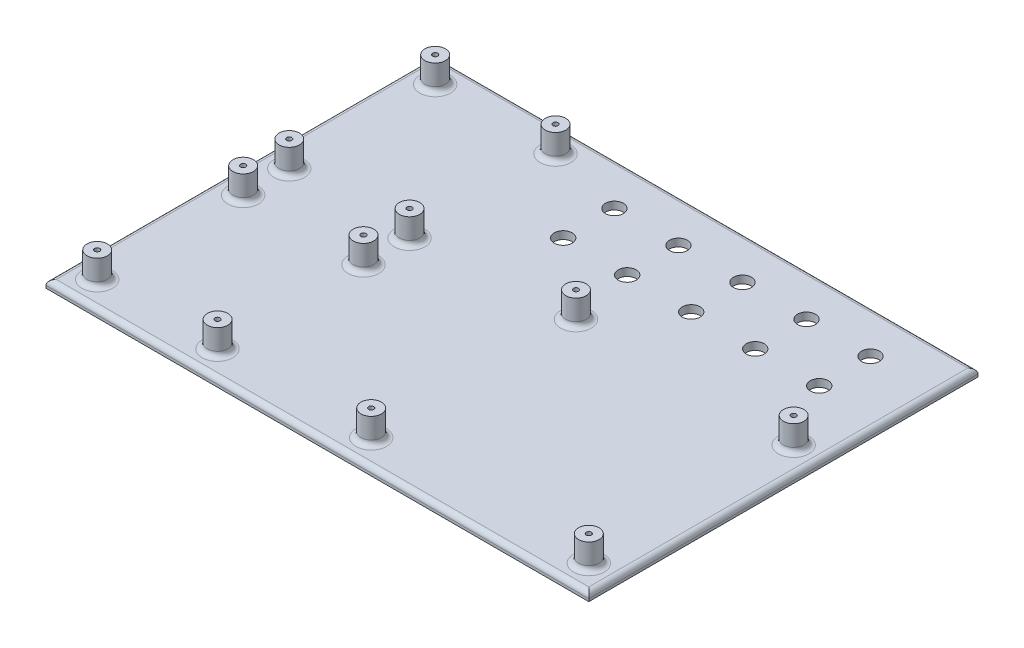
SolidWorks part; units mm, degrees
ref_plane "Front Plane" through (0, 0, 0) normal (0, 0, 1) x (1, 0, 0)
ref_plane "Top Plane" through (0, 0, 0) normal (0, 1, 0) x (1, 0, 0)
ref_plane "Right Plane" through (0, 0, 0) normal (1, 0, 0) x (0, 0, -1)
sketch "Sketch1" plane through (0, 0, 0) normal (0, 1, 0) x (1, 0, 0)
  circle A0 centre (0, 0) radius 4
  circle A1 centre (0, 80) radius 4
  circle A2 centre (85, 80) radius 4
  circle A3 centre (85, 0) radius 4
  circle A4 centre (-107, 0) radius 4
  circle A5 centre (-60, 0) radius 4
  circle A6 centre (-60, 57) radius 4
  circle A7 centre (-107, 57) radius 4
  circle A8 centre (-107, 132) radius 4
  circle A9 centre (-60, 132) radius 4
  circle A10 centre (-60, 75) radius 4
  circle A11 centre (-107, 75) radius 4
  dimension "D1" = 8
  dimension "D2" = 85
  dimension "D3" = 80
  dimension "D4" = 47
  dimension "D5" = 57
  dimension "D6" = 60
  dimension "D8" = 18
  dimension "D7" = 2
extrude "Boss-Extrude1" add sketch "Sketch1" along normal blind 10
sketch "Sketch2" plane through (0, 0, 0) normal (0, 1, 0) x (1, 0, 0)
  line L1 (-117, 142) -> (95, 142)
  line L2 (-117, 142) -> (-117, -10)
  line L3 (-117, -10) -> (95, -10)
  line L4 (95, 142) -> (95, -10)
  circle A0 centre (85, 0) radius 4 construction
  circle A1 centre (-60, 132) radius 4 construction
  circle A2 centre (-107, 0) radius 4 construction
  point P4 (131.0128, -48.0077)
  dimension "D1" = 10
  dimension "D2" = 10
  dimension "D3" = 10
  dimension "D4" = 10
extrude "Boss-Extrude2" add sketch "Sketch2" against normal blind 3
fillet "Fillet1" radius 2 16 edges at (-11, 0, -142) (95, 0, -66) (-11, 0, 10) (-117, 0, -66) (0, 0, 4) (0, 0, -76) (85, 0, -76) (85, 0, 4) (-60, 0, 4) (-60, 0, -53) (-107, 0, 4) (-107, 0, -53) (-60, 0, -71) (-60, 0, -128) (-107, 0, -71) (-107, 0, -128)
sketch "Sketch3" plane through (0, 0, 0) normal (0, 1, 0) x (1, 0, 0)
  circle A0 centre (-30, 125) radius 3.5
  circle A1 centre (-30, 105) radius 3.5
  circle A2 centre (0, 80) radius 4 construction
  circle A3 centre (-60, 132) radius 4 construction
  circle A4 centre (-5, 105) radius 3.5
  circle A5 centre (-5, 125) radius 3.5
  circle A6 centre (20, 105) radius 3.5
  circle A7 centre (20, 125) radius 3.5
  circle A8 centre (45, 105) radius 3.5
  circle A9 centre (45, 125) radius 3.5
  circle A10 centre (70, 105) radius 3.5
  circle A11 centre (70, 125) radius 3.5
  dimension "D2" = 7
  dimension "D4" = 30
  dimension "D6" = 25
  dimension "D1" = 20
  dimension "D3" = 25
  dimension "D5" = 5
extrude "Cut-Extrude1" cut sketch "Sketch3" against normal through all both and the other way through all
hole_wizard "Ø2.0mm Dowel Hole1" positions "Sketch4" profile "Sketch5" hole size "Ø2.0" standard "ANSI Metric" end condition through all
sketch "Sketch4" plane through (0, 10, 0) normal (0, 1, 0) x (1, 0, 0)
  point P0 (-107, 132)
  point P3 (-60, 132)
  point P6 (-60, 75)
  point P9 (-107, 75)
  point P12 (-60, 57)
  point P15 (-107, 57)
  point P18 (-107, 0)
  point P21 (-60, 0)
  point P24 (0, 0)
  point P27 (85, 0)
  point P30 (85, 80)
  point P33 (0, 80)
sketch "Sketch5" plane through (-107, 10, -132) normal (1, 0, 0) x (0, 0, 1)
  line L0 (0, 0) -> (0, 13)
  line L1 (0, 13) -> (1, 13)
  line L2 (1, 13) -> (1, 0)
  line L5 (1, 0) -> (0, 0)
  line L11 (0, -6.35) -> (0, 107.95) construction
  dimension "Thru Hole Dia." = 2
  dimension "Thru Hole Depth" = 13
